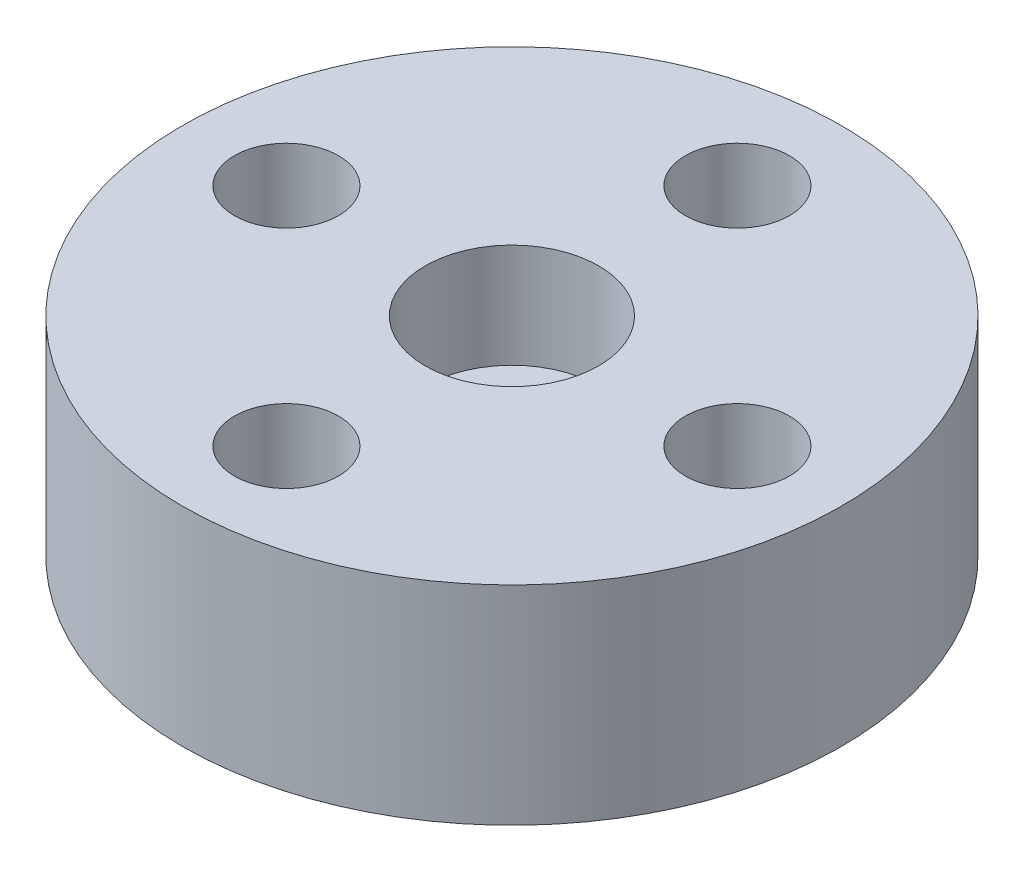
SolidWorks part; units mm, degrees
ref_plane "Front Plane" through (0, 0, 0) normal (0, 0, 1) x (1, 0, 0)
ref_plane "Top Plane" through (0, 0, 0) normal (0, 1, 0) x (1, 0, 0)
ref_plane "Right Plane" through (0, 0, 0) normal (1, 0, 0) x (0, 0, -1)
sketch "Sketch1" plane through (0, 0, 0) normal (0, 1, 0) x (1, 0, 0)
  circle A0 centre (0, 0) radius 9.5
  circle A1 centre (6.5, 0) radius 1.5
  circle A2 centre (0, -6.5) radius 1.5
  circle A3 centre (-6.5, 0) radius 1.5
  circle A4 centre (0, 6.5) radius 1.5
  dimension "D1" = 19
  dimension "D2" = 3
  dimension "D3" = 6.5
  dimension "D4" = 4
extrude "Boss-Extrude1" add sketch "Sketch1" along normal blind 6
sketch "Sketch2" plane through (0, 6, 0) normal (0, 1, 0) x (1, 0, 0)
  circle A0 centre (0, 0) radius 2.5
  dimension "D1" = 5
extrude "Cut-Extrude1" cut sketch "Sketch2" against normal blind 3
